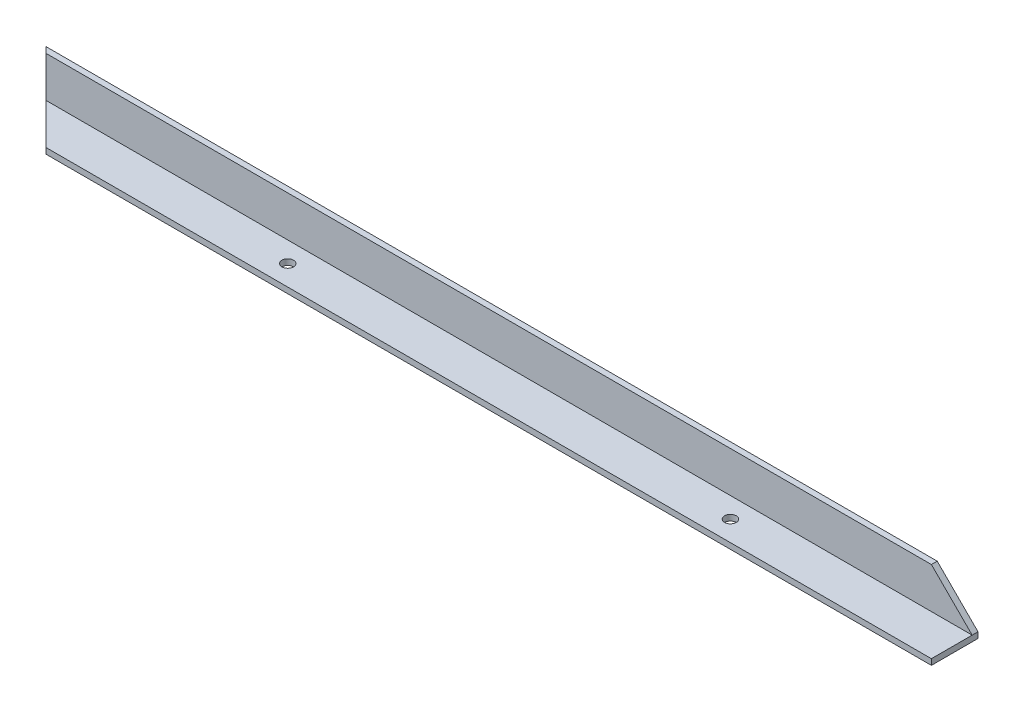
SolidWorks part; units mm, degrees
ref_plane "Front Plane" through (0, 0, 0) normal (0, 0, 1) x (1, 0, 0)
ref_plane "Top Plane" through (0, 0, 0) normal (0, 1, 0) x (1, 0, 0)
ref_plane "Right Plane" through (0, 0, 0) normal (1, 0, 0) x (0, 0, -1)
sketch "Sketch1" plane through (0, 0, 0) normal (0, 1, 0) x (1, 0, 0)
  line L1 (0, 0) -> (-508, 0)
  line L2 (0, 0) -> (0, -25.4)
  line L3 (0, -25.4) -> (-508, -25.4)
  line L4 (-508, 0) -> (-508, -25.4)
  dimension "D1" = 508
  dimension "D2" = 25.4
extrude "Boss-Extrude1" add sketch "Sketch1" along normal blind 3.175
sketch "Sketch2" plane through (0, 3.175, 0) normal (0, 1, 0) x (1, 0, 0)
  line L0 (0, -25.4) -> (0, 0) construction
  line L1 (-508, 0) -> (0, 0)
  line L2 (-508, 0) -> (-508, -3.175)
  line L3 (-508, -3.175) -> (0, -3.175)
  line L4 (0, 0) -> (0, -3.175)
  dimension "D1" = 3.175
extrude "Boss-Extrude2" add sketch "Sketch2" along normal blind 22.225
sketch "Sketch7" plane through (0, 25.4, 0) normal (0, 1, 0) x (1, 0, 0)
  line L0 (-508, 0) -> (-465.1142, -42.8858)
  line L1 (-465.1142, -42.8858) -> (-525.0287, -42.8858)
  line L2 (-525.0287, -42.8858) -> (-508, 0)
  line L3 (0, 0) -> (-508, 0) construction
  dimension "D1" = 45
extrude "Cut-Extrude4" cut sketch "Sketch7" against normal up to surface (25.4 mm away) up to face at (-254, 0, 12.7)
sketch "Sketch8" plane through (0, 0, 3.175) normal (0, 0, 1) x (1, 0, 0)
  line L0 (0, 3.175) -> (-40.6514, 43.8264)
  line L1 (-40.6514, 43.8264) -> (40.603, 27.1293)
  line L2 (40.603, 27.1293) -> (0, 3.175)
  line L3 (-504.825, 3.175) -> (0, 3.175) construction
  dimension "D1" = 45
extrude "Cut-Extrude5" cut sketch "Sketch8" against normal blind 22.225
sketch "Sketch9" plane through (0, 3.175, 0) normal (0, 1, 0) x (1, 0, 0)
  line L0 (-241.3, -25.4) -> (-241.3, -3.175) construction
  line L1 (-482.6, -25.4) -> (0, -25.4) construction
  line L2 (-504.825, -3.175) -> (-22.225, -3.175) construction
  circle A0 centre (-361.95, -14.2875) radius 3.175
  circle A1 centre (-120.65, -14.2875) radius 3.175
  dimension "D1" = 6.35
  dimension "D2" = 22.225
  dimension "D3" = 11.1125
  dimension "D4" = 241.3
  dimension "D5" = 120.65
extrude "Cut-Extrude6" cut sketch "Sketch9" against normal up to surface (3.175 mm away) up to face at (-247.65, 0, 12.7)
